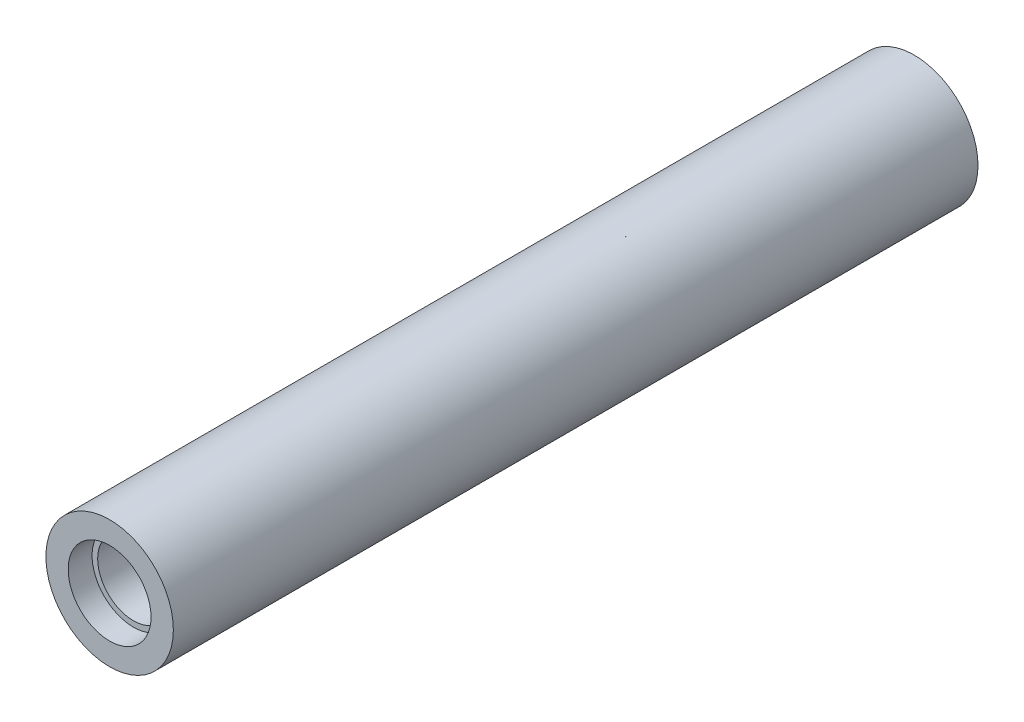
SolidWorks part; units mm, degrees
material "Lega 1350"
ref_plane "Piano frontale" through (0, 0, 0) normal (0, 0, 1) x (1, 0, 0)
ref_plane "Piano superiore" through (0, 0, 0) normal (0, 1, 0) x (1, 0, 0)
ref_plane "Piano destro" through (0, 0, 0) normal (1, 0, 0) x (0, 0, -1)
sketch "Schizzo1" plane through (0, 0, 0) normal (0, 0, 1) x (1, 0, 0)
  circle A0 centre (0, 0) radius 40
  circle A1 centre (0, 0) radius 22.5
  dimension "D1" = 80
  dimension "D2" = 45
extrude "Estrusione1" add sketch "Schizzo1" along normal mid plane 505
sketch "Schizzo2" plane through (0, 0, 252.5) normal (0, 0, 1) x (1, 0, 0)
  circle A0 centre (0, 0) radius 26
  circle A1 centre (0, 0) radius 22.5 construction
  circle A2 centre (0, 0) radius 22.5
  dimension "D1" = 52
extrude "Taglio-Estrusione1" cut sketch "Schizzo2" against normal blind 15
sketch "Schizzo3" plane through (0, 0, -252.5) normal (0, 0, -1) x (-1, 0, 0)
  circle A0 centre (0, 0) radius 22.5 construction
  circle A1 centre (0, 0) radius 26 construction
  circle A2 centre (0, 0) radius 22.5
  circle A3 centre (0, 0) radius 26
extrude "Taglio-Estrusione2" cut sketch "Schizzo3" against normal blind 15
